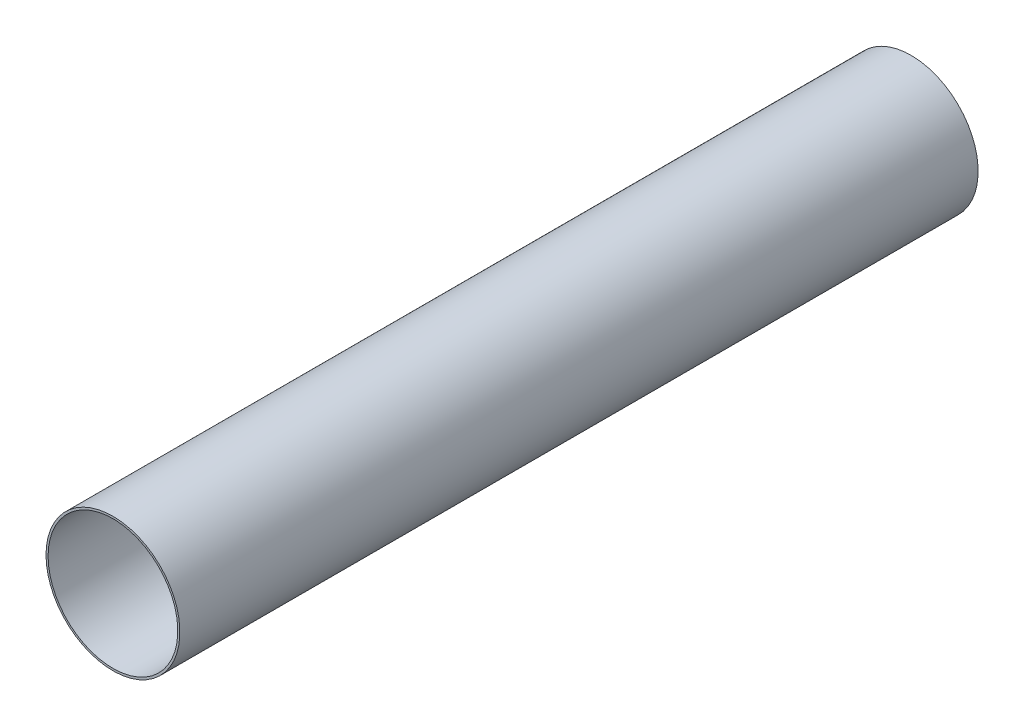
SolidWorks part; units mm, degrees
material "Thornel Mat VMA"
ref_plane "Front Plane" through (0, 0, 0) normal (0, 0, 1) x (1, 0, 0)
ref_plane "Top Plane" through (0, 0, 0) normal (0, 1, 0) x (1, 0, 0)
ref_plane "Right Plane" through (0, 0, 0) normal (1, 0, 0) x (0, 0, -1)
sketch "Sketch1" plane through (0, 0, 0) normal (0, 0, 1) x (1, 0, 0)
  circle A0 centre (0, 0) radius 51.1175
  circle A1 centre (0, 0) radius 49.53
  dimension "D1" = 1.5875
  dimension "D2" = 102.235
extrude "Boss-Extrude1" add sketch "Sketch1" along normal blind 609.6
